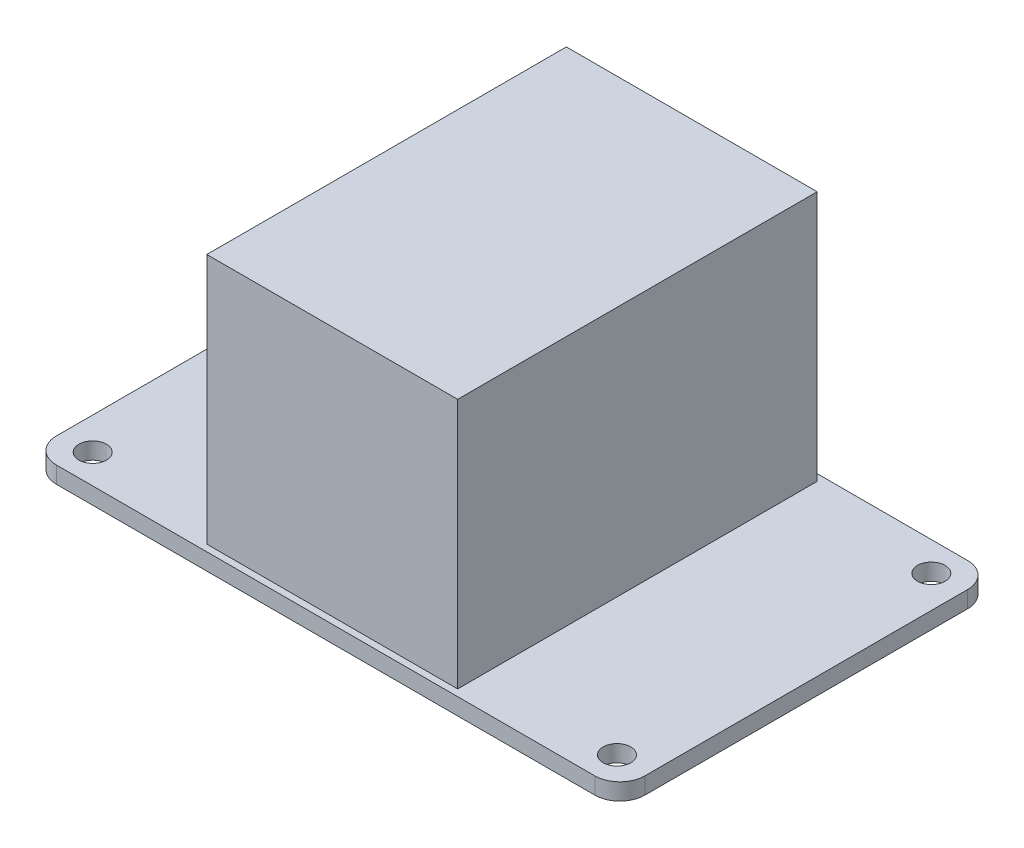
SolidWorks part; units mm, degrees
ref_plane "Front Plane" through (0, 0, 0) normal (0, 0, 1) x (1, 0, 0)
ref_plane "Top Plane" through (0, 0, 0) normal (0, 1, 0) x (1, 0, 0)
ref_plane "Right Plane" through (0, 0, 0) normal (1, 0, 0) x (0, 0, -1)
sketch "Sketch1" plane through (0, 0, 0) normal (0, 1, 0) x (1, 0, 0)
  line L1 (-35.2, -22.3) -> (35.2, -22.3)
  line L2 (-35.2, -22.3) -> (-35.2, 22.3)
  line L3 (-35.2, 22.3) -> (35.2, 22.3)
  line L4 (35.2, -22.3) -> (35.2, 22.3)
  line L5 (-35.2, -22.3) -> (35.2, 22.3) construction
  line L6 (-35.2, 22.3) -> (35.2, -22.3) construction
  point P0 (0, 0)
  dimension "D1" = 44.6
  dimension "D2" = 70.4
extrude "Boss-Extrude1" add sketch "Sketch1" along normal blind 2
sketch "Sketch3" plane through (0, 2, 0) normal (0, 1, 0) x (1, 0, 0)
  line L0 (-31.35, 18.8) -> (31.35, -18.8) construction
  line L1 (31.35, 18.8) -> (-31.35, -18.8) construction
  line L12 (31.35, -18.8) -> (31.35, 18.8) construction
  line L13 (31.35, 18.8) -> (-31.35, 18.8) construction
  line L14 (-31.35, 18.8) -> (-31.35, -18.8) construction
  line L15 (-31.35, -18.8) -> (31.35, -18.8) construction
  circle A0 centre (-31.35, 18.8) radius 1.65
  circle A1 centre (31.35, 18.8) radius 1.65
  circle A2 centre (31.35, -18.8) radius 1.65
  circle A3 centre (-31.35, -18.8) radius 1.65
  point P4 (-33, 18.8)
  point P5 (33, 18.8)
  point P7 (0, 0)
  point P9 (-31.35, 20.45)
  point P13 (-31.35, -20.45)
  point P14 (0, 0)
  point P15 (0, 0)
  point P16 (31.5844, -14.9037)
  point P17 (-33, 18.8)
  dimension "D2" = 3.3
  dimension "D1" = 66
  dimension "D3" = 40.9
extrude "Cut-Extrude1" cut sketch "Sketch3" against normal through all contours A0
fillet "Fillet1" radius 3 4 edges at (35.2, 1, -22.3) (35.2, 1, 22.3) (-35.2, 1, -22.3) (-35.2, 1, 22.3)
sketch "Sketch4" plane through (0, 2, 0) normal (0, 1, 0) x (1, 0, 0)
  line L1 (-15, -21.5) -> (15, -21.5)
  line L2 (-15, -21.5) -> (-15, 21.5)
  line L3 (-15, 21.5) -> (15, 21.5)
  line L4 (15, -21.5) -> (15, 21.5)
  line L5 (-15, -21.5) -> (15, 21.5) construction
  line L6 (-15, 21.5) -> (15, -21.5) construction
  point P0 (0, 0)
  dimension "D1" = 30
  dimension "D2" = 43
extrude "Boss-Extrude2" add sketch "Sketch4" along normal blind 30
